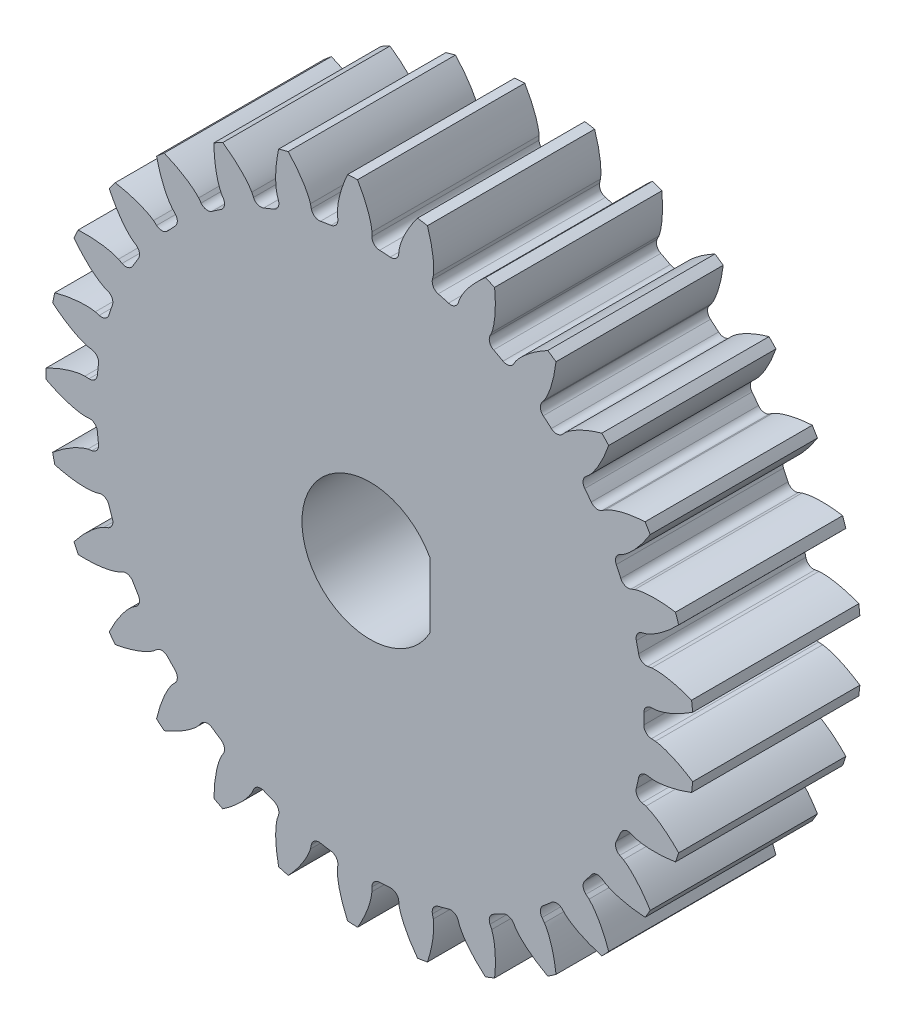
SolidWorks part; units mm, degrees
ref_plane "Front Plane" through (0, 0, 0) normal (0, 0, 1) x (1, 0, 0)
ref_plane "Top Plane" through (0, 0, 0) normal (0, 1, 0) x (1, 0, 0)
ref_plane "Right Plane" through (0, 0, 0) normal (1, 0, 0) x (0, 0, -1)
ref_axis "Gear Axis" through (0, 0, -0.5001) along (0, 0, 1)
sketch "Blank Sketch" plane through (0, 0, 0) normal (0, 0, 1) x (1, 0, 0)
  circle A0 centre (0, 0) radius 19.375
  dimension "OD" = 38.75
extrude "Blank" add sketch "Blank Sketch" along normal blind 10
sketch "Tooth Space Sketch" plane through (0, 0, 0) normal (0, 0, 1) x (1, 0, 0)
  line L0 (17.0681, 0.815) -> (16.8241, 0.8033)
  line L1 (17.0681, -0.815) -> (16.8241, -0.8033)
  line L2 (20.4475, 2.7002) -> (20.4475, -2.7002)
  arc A0 (16.8241, 0.8033) -> (16.3719, 0.3196) centre (16.8468, 0.3289) ccw
  arc A1 (16.3719, -0.3196) -> (16.8241, -0.8033) centre (16.8468, -0.3289) ccw
  arc A2 (16.3719, -0.3196) -> (16.3719, 0.3196) centre (0, 0) ccw
  spline S0 degree 4 poles (17.0152, 0.8094) (17.031, 0.8108) (17.0595, 0.8136) (17.094, 0.8183) (17.1722, 0.8309) (17.2433, 0.8458) (17.3432, 0.8685) (17.4448, 0.8961) (17.5609, 0.9304) (17.6753, 0.9684) (17.7907, 1.0095) (17.9039, 1.053) (18.0313, 1.1052) (18.1847, 1.1722) (18.3644, 1.257) (18.5674, 1.3607) (18.7814, 1.4793) (18.9895, 1.6023) (19.1976, 1.7344) (19.3963, 1.8669) (19.6008, 2.0129) (19.7864, 2.15) (19.9939, 2.3143) (20.156, 2.4454) (20.3728, 2.6331) (20.4919, 2.7394) (20.6352, 2.8713) (20.6979, 2.9311) (20.7349, 2.9665) knots 0 0 0 0 0 0.011935 0.024895 0.042157 0.060774 0.086082 0.114007 0.141932 0.169857 0.197782 0.225707 0.253632 0.295827 0.351677 0.407526 0.463377 0.519226 0.575076 0.630926 0.686776 0.742626 0.798476 0.854326 0.910176 0.955088 1 1 1 1 1 construction
  spline S1 degree 4 poles (17.0681, 0.815) (17.0806, 0.8166) (17.1094, 0.8208) (17.1722, 0.8309) (17.2433, 0.8458) (17.3432, 0.8685) (17.4448, 0.8961) (17.5609, 0.9304) (17.6753, 0.9684) (17.7907, 1.0095) (17.9039, 1.053) (18.0313, 1.1052) (18.1847, 1.1722) (18.3644, 1.257) (18.5674, 1.3607) (18.7814, 1.4793) (18.9895, 1.6023) (19.1976, 1.7344) (19.3963, 1.8669) (19.6008, 2.0129) (19.7864, 2.15) (19.9939, 2.3143) (20.156, 2.4454) (20.327, 2.5934) (20.4067, 2.6637) (20.4475, 2.7002) knots 0.011935 0.011935 0.011935 0.011935 0.011935 0.024895 0.042157 0.060774 0.086082 0.114007 0.141932 0.169857 0.197782 0.225707 0.253632 0.295827 0.351677 0.407526 0.463377 0.519226 0.575076 0.630926 0.686776 0.742626 0.798476 0.854326 0.910176 0.910176 0.910176 0.910176 0.910176
  spline S2 degree 4 poles (17.0152, -0.8094) (17.031, -0.8108) (17.0595, -0.8136) (17.094, -0.8183) (17.1722, -0.8309) (17.2433, -0.8458) (17.3432, -0.8685) (17.4448, -0.8961) (17.5609, -0.9304) (17.6753, -0.9684) (17.7907, -1.0095) (17.9039, -1.053) (18.0313, -1.1052) (18.1847, -1.1722) (18.3644, -1.257) (18.5674, -1.3607) (18.7814, -1.4793) (18.9895, -1.6023) (19.1976, -1.7344) (19.3963, -1.8669) (19.6008, -2.0129) (19.7864, -2.15) (19.9939, -2.3143) (20.156, -2.4454) (20.3728, -2.6331) (20.4919, -2.7394) (20.6352, -2.8713) (20.6979, -2.9311) (20.7349, -2.9665) knots 0 0 0 0 0 0.011935 0.024895 0.042157 0.060774 0.086082 0.114007 0.141932 0.169857 0.197782 0.225707 0.253632 0.295827 0.351677 0.407526 0.463377 0.519226 0.575076 0.630926 0.686776 0.742626 0.798476 0.854326 0.910176 0.955088 1 1 1 1 1 construction
  spline S3 degree 4 poles (17.0681, -0.815) (17.0806, -0.8166) (17.1094, -0.8208) (17.1722, -0.8309) (17.2433, -0.8458) (17.3432, -0.8685) (17.4448, -0.8961) (17.5609, -0.9304) (17.6753, -0.9684) (17.7907, -1.0095) (17.9039, -1.053) (18.0313, -1.1052) (18.1847, -1.1722) (18.3644, -1.257) (18.5674, -1.3607) (18.7814, -1.4793) (18.9895, -1.6023) (19.1976, -1.7344) (19.3963, -1.8669) (19.6008, -2.0129) (19.7864, -2.15) (19.9939, -2.3143) (20.156, -2.4454) (20.327, -2.5934) (20.4067, -2.6637) (20.4475, -2.7002) knots 0.011935 0.011935 0.011935 0.011935 0.011935 0.024895 0.042157 0.060774 0.086082 0.114007 0.141932 0.169857 0.197782 0.225707 0.253632 0.295827 0.351677 0.407526 0.463377 0.519226 0.575076 0.630926 0.686776 0.742626 0.798476 0.854326 0.910176 0.910176 0.910176 0.910176 0.910176
  dimension "Root" = 16.375
  dimension "Fillet" = 0.475
extrude "Tooth Space" cut sketch "Tooth Space Sketch" against normal through all both and the other way through all both
pattern_circular "Teeth" count 29 over 360 about axis through (0, 0, -0.5001) along (0, 0, 1) of "Tooth Space"
sketch "Bore Sketch" plane through (0, 0, 0) normal (0, 0, 1) x (1, 0, 0)
  circle A0 centre (0, 0) radius 4.075
  dimension "Bore" = 8.15
extrude "Bore" cut sketch "Bore Sketch" against normal through all both and the other way through all both
sketch "D-Flat Sketch" plane through (0, 0, 0) normal (0, 0, 1) x (1, 0, 0)
  line L0 (3.575, -2.3894) -> (3.575, 2.3894)
  arc A0 (3.575, -2.3894) -> (3.575, 2.3894) centre (0, 0) ccw
extrude "D-Flat" add sketch "D-Flat Sketch" along normal blind 10
equation "\"No. of Teeth\"= 29"
equation "\"Module\"= 1.25"
equation "\"Bore Diameter\"= 8.15"
equation "\"Pressure Angle\"= 20"
equation "\"Outer Diameter\"= ( \"No. of Teeth\" + 2 ) * \"Module\""
equation "\"Pitch Diameter\"= \"No. of Teeth\" * \"Module\""
equation "\"Backlash\"= IIF ( \"Module\" <= 1 , 0.3 * \"Module\" , 0.3 )"
equation "\"Arc Length\"= ( ( \"Module\" * pi ) / 2 + \"Backlash\" )"
equation "\"Fillet Radius\"= 0.38 * \"Module\""
equation "\"Tooth Depth\"= IIF ( \"Module\" <= 1.25 , \"Module\" * 2.4 , \"Module\" * 2.25 )"
equation "\"Face Width\"= 10"
equation "\"Root Diameter\"= \"Outer Diameter\" - 2 * \"Tooth Depth\""
equation "\"Base Diameter\"= \"Pitch Diameter\" * cos ( \"Pressure Angle\" )"
equation "\"Base Radius\"= \"Base Diameter\" / 2"
equation "\"Tooth Thickness\"= \"Module\" * pi - \"Arc Length\""
equation "\"Half Space Angle\"= ( \"Arc Length\" / \"Pitch Diameter\" ) * 180 / pi"
equation "\"Involute Fn\"= tan ( \"Pressure Angle\" ) - \"Pressure Angle\" * pi / 180"
equation "\"Flank Offset\"= \"Arc Length\" / \"Pitch Diameter\" - \"Involute Fn\""
equation "\"Tip Cap Diameter\"= \"Outer Diameter\" + 2 * \"Module\""
equation "\"Flank Start Diameter\"= IIF ( \"Base Diameter\" >= ( \"Root Diameter\" + 3 * \"Fillet Radius\" ) , \"Base Diameter\" , \"Root Diameter\" + 3 * \"Fillet Radius\" )"
equation "\"Involute t1\"= ( abs ( ( \"Flank Start Diameter\" / \"Base Diameter\" ) ^ 2 - 1 ) ) ^ 0.5"
equation "\"Involute t2\"= ( abs ( ( \"Tip Cap Diameter\" / \"Base Diameter\" ) ^ 2 - 1 ) ) ^ 0.5"
equation "\"Flank Arc Radius\"= ( \"Pitch Diameter\" / 2 ) * sin ( \"Pressure Angle\" )"
equation "\"Flank Centre Angle\"= \"Half Space Angle\" + \"Pressure Angle\""
equation "\"OD@Blank Sketch\"= \"Outer Diameter\""
equation "\"Width@Blank\"= \"Face Width\""
equation "\"Root@Tooth Space Sketch\"= \"Root Diameter\" / 2"
equation "\"Fillet@Tooth Space Sketch\"= \"Fillet Radius\""
equation "\"Count@Teeth\"= \"No. of Teeth\""
equation "\"Bore@Bore Sketch\"= \"Bore Diameter\""
